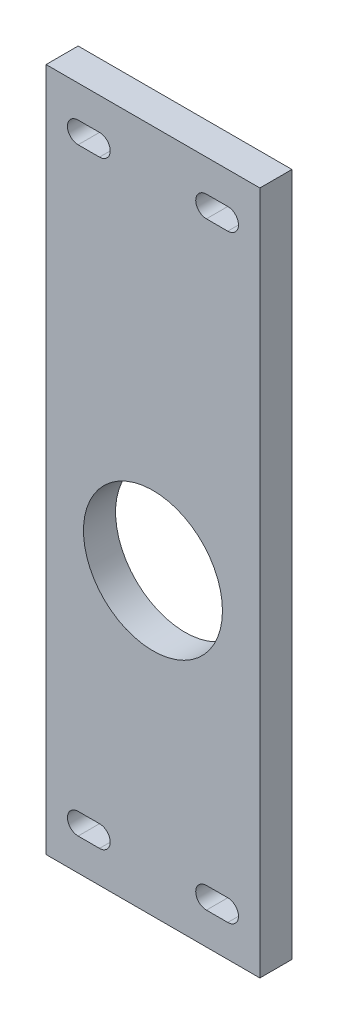
SolidWorks part; units mm, degrees
ref_plane "Front Plane" through (0, 0, 0) normal (0, 0, 1) x (1, 0, 0)
ref_plane "Top Plane" through (0, 0, 0) normal (0, 1, 0) x (1, 0, 0)
ref_plane "Right Plane" through (0, 0, 0) normal (1, 0, 0) x (0, 0, -1)
sketch "Sketch1" plane through (0, 0, 0) normal (0, 0, 1) x (1, 0, 0)
  line L1 (-31.75, 101.6) -> (31.75, 101.6)
  line L2 (-31.75, 101.6) -> (-31.75, -101.6)
  line L3 (-31.75, -101.6) -> (31.75, -101.6)
  line L4 (31.75, 101.6) -> (31.75, -101.6)
  line L5 (-31.75, 101.6) -> (31.75, -101.6) construction
  line L6 (-31.75, -101.6) -> (31.75, 101.6) construction
  point P0 (0, 0)
  dimension "D1" = 63.5
  dimension "D2" = 203.2
extrude "Boss-Extrude1" add sketch "Sketch1" along normal blind 9.525
sketch "Sketch2" plane through (0, 0, 9.525) normal (0, 0, 1) x (1, 0, 0)
  line L0 (-31.75, 101.6) -> (-31.75, -101.6) construction
  line L1 (31.75, 101.6) -> (-31.75, 101.6) construction
  line L2 (-22.225, 88.9) -> (-15.875, 88.9) construction
  line L3 (-22.225, 92.075) -> (-15.875, 92.075)
  line L4 (-22.225, 85.725) -> (-15.875, 85.725)
  circle A0 centre (-19.05, 88.9) radius 3.175 construction
  arc A1 (-22.225, 92.075) -> (-22.225, 85.725) centre (-22.225, 88.9) ccw
  arc A2 (-15.875, 85.725) -> (-15.875, 92.075) centre (-15.875, 88.9) ccw
  point P8 (-19.05, 88.9)
  dimension "D3" = 6.35
  dimension "D1" = 12.7
  dimension "D2" = 12.7
  dimension "D4" = 6.35
extrude "Cut-Extrude1" cut sketch "Sketch2" against normal through all
pattern_linear "LPattern1" count 2 spacing 38.1 along (1, 0, 0) count 2 spacing 177.8 along (0, -1, 0) of "Cut-Extrude1"
sketch "Sketch3" plane through (0, 0, 9.525) normal (0, 0, 1) x (1, 0, 0)
  line L0 (31.75, -101.6) -> (31.75, 101.6) construction
  line L1 (-31.75, -101.6) -> (31.75, -101.6) construction
  circle A0 centre (0, -12.7) radius 20.6375
  dimension "D1" = 41.275
  dimension "D3" = 88.9
  dimension "D2" = 31.75
extrude "Cut-Extrude2" cut sketch "Sketch3" against normal through all
